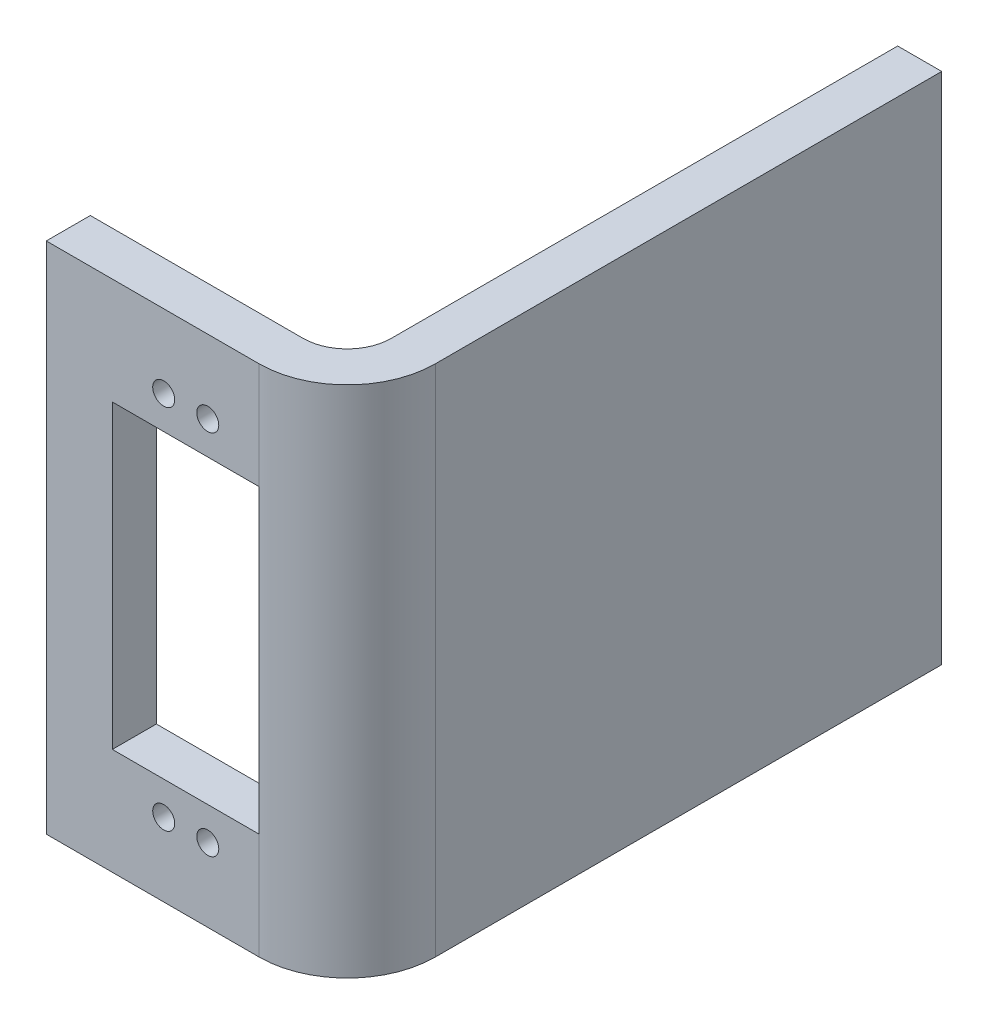
SolidWorks part; units mm, degrees
material "Acrilico TEC"
ref_plane "Front Plane" through (0, 0, 0) normal (0, 0, 1) x (1, 0, 0)
ref_plane "Top Plane" through (0, 0, 0) normal (0, 1, 0) x (1, 0, 0)
ref_plane "Right Plane" through (0, 0, 0) normal (1, 0, 0) x (0, 0, -1)
sketch "Sketch2" plane through (0, 0, 0) normal (0, 1, 0) x (1, 0, 0)
  line L0 (6, 0) -> (6, -69)
  line L1 (0, 0) -> (0, -69)
  line L2 (-6, -75) -> (-35, -75)
  line L3 (-35, -75) -> (-35, -81)
  line L4 (-6, -81) -> (-35, -81)
  line L5 (0, 0) -> (6, 0)
  arc A0 (0, -69) -> (-6, -75) centre (-6, -69) cw
  arc A1 (6, -69) -> (-6, -81) centre (-6, -69) cw
  point P8 (0, -75)
  dimension "D4" = 6
  dimension "D1" = 75
  dimension "D2" = 35
  dimension "D3" = 6
  dimension "D5" = 6
extrude "Boss-Extrude1" add sketch "Sketch2" along normal blind 70 contours A1 L0 L5 L1 A0 L2 L3 L4
sketch "Sketch3" plane through (0, 0, 81) normal (0, 0, 1) x (1, 0, 0)
  line L0 (-35, 35) -> (-6, 35) construction
  line L1 (-35, 70) -> (-35, 0) construction
  line L2 (-6, 70) -> (-6, 0) construction
  line L3 (-16, 14.5) -> (-16, 55.5) construction
  line L4 (-13, 10) -> (-19, 10) construction
  line L5 (-16, 10) -> (-16, 60) construction
  line L6 (-16, 60) -> (-19, 60) construction
  line L7 (-26, 55.5) -> (-6, 55.5)
  line L8 (-26, 55.5) -> (-26, 14.5)
  line L9 (-26, 14.5) -> (-6, 14.5)
  line L10 (-6, 55.5) -> (-6, 14.5)
  line L11 (-26, 55.5) -> (-6, 14.5) construction
  line L12 (-26, 14.5) -> (-6, 55.5) construction
  circle A0 centre (-19, 60) radius 1.5
  circle A1 centre (-13, 60) radius 1.5
  circle A2 centre (-13, 10) radius 1.5
  circle A3 centre (-19, 10) radius 1.5
  point P20 (-23, 35)
  dimension "D1" = 3
  dimension "D2" = 25
  dimension "D3" = 6
  dimension "D4" = 20
  dimension "D5" = 41
  dimension "D6" = 10
extrude "Cut-Extrude1" cut sketch "Sketch3" against normal blind 50
